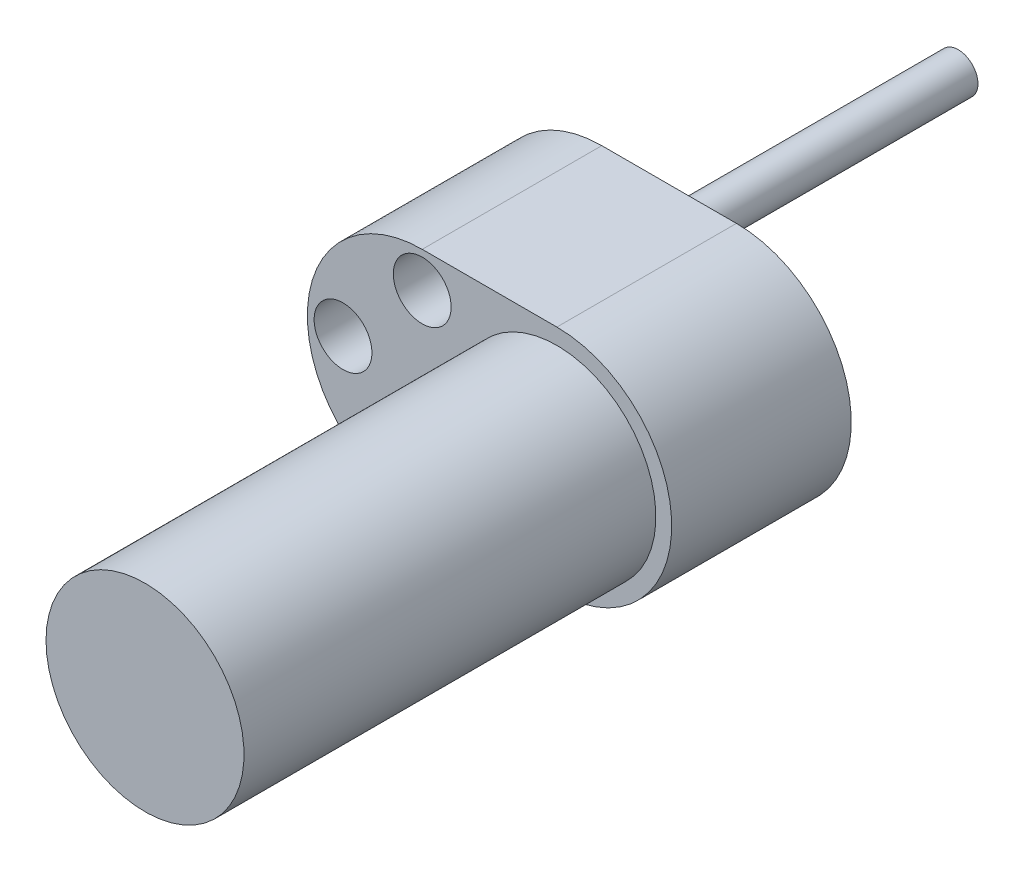
SolidWorks part; units mm, degrees
material "1060 合金"
ref_plane "前视基准面" through (0, 0, 0) normal (0, 0, 1) x (1, 0, 0)
ref_plane "上视基准面" through (0, 0, 0) normal (0, 1, 0) x (1, 0, 0)
ref_plane "右视基准面" through (0, 0, 0) normal (1, 0, 0) x (0, 0, -1)
other "Configuration Table"
sketch "草图1" plane through (0, 0, 0) normal (0, 0, 1) x (1, 0, 0)
  line L1 (-31.5, 35.5) -> (-14.5, 35.5)
  line L2 (-31.5, 6.5) -> (-14.5, 6.5)
  line L3 (-14.5, 6.5) -> (-14.5, 35.5) construction
  arc A10 (-31.5, 35.5) -> (-31.5, 6.5) centre (-31.5, 21) ccw
  arc A11 (-14.5, 6.5) -> (-14.5, 35.5) centre (-14.5, 21) ccw
  dimension "D1" = 14.5
  dimension "D2" = 14.5
  dimension "D3" = 14.5
  dimension "D4" = 6.5
  dimension "D5" = 17
  dimension "D6" = 17
extrude "凸台-拉伸1" add sketch "草图1" along normal blind 22.67
sketch "草图3" plane through (0, 0, 0) normal (0, 0, -1) x (-1, 0, 0)
  line L0 (31.5, 35.5) -> (31.5, 6.5) construction
  line L1 (31.5, 21) -> (46, 21) construction
  circle A3 centre (31.5, 11) radius 3.65
  circle A4 centre (31.5, 31) radius 3.65
  circle A5 centre (41.5, 21) radius 3.65
  arc A6 (31.5, 6.5) -> (31.5, 35.5) centre (31.5, 21) ccw construction
  dimension "D1" = 7.3
  dimension "D2" = 7.3
  dimension "D3" = 7.3
  dimension "D4" = 4.5
  dimension "D5" = 4.5
  dimension "D6" = 4.5
extrude "切除-拉伸1" cut sketch "草图3" against normal blind 22.67
sketch "草图7" plane through (0, 0, 0) normal (0, 0, -1) x (-1, 0, 0)
  line L0 (31.5, 35.5) -> (31.5, 6.5) construction
  circle A1 centre (31.5, 21) radius 2.5
  dimension "D1" = 5
  dimension "D2" = 14.5
extrude "凸台-拉伸2" add sketch "草图7" along normal blind 45
sketch "草图8" plane through (0, 0, 22.67) normal (0, 0, 1) x (1, 0, 0)
  circle A1 centre (-14.5, 21) radius 12.5
  dimension "D1" = 25
extrude "凸台-拉伸3" add sketch "草图8" along normal blind 52
